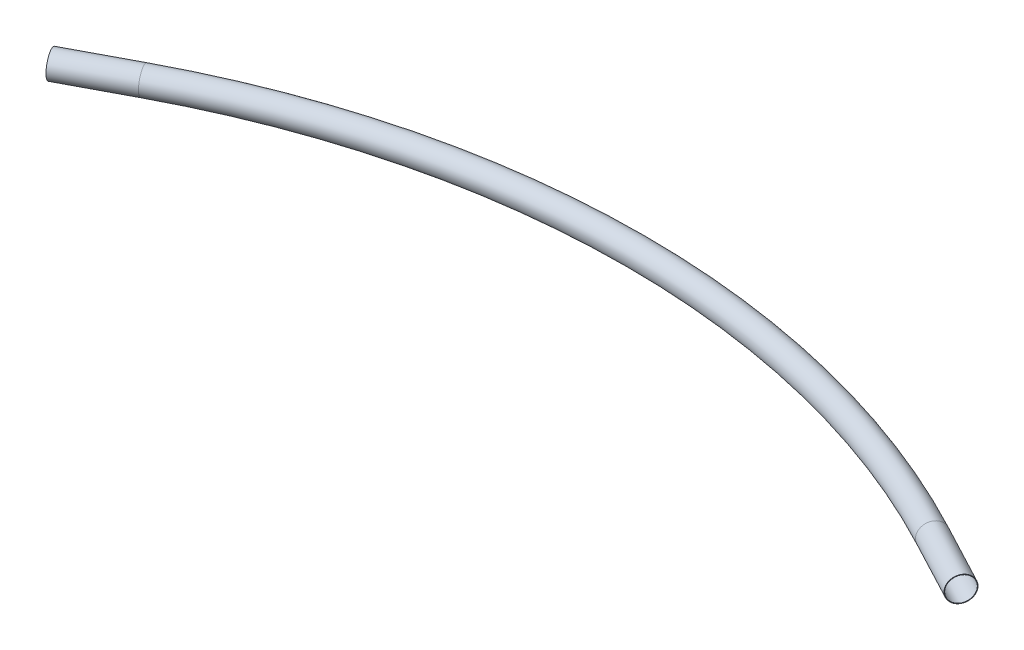
SolidWorks part; units mm, degrees
ref_plane "Front Plane" through (0, 0, 0) normal (0, 0, 1) x (1, 0, 0)
ref_plane "Top Plane" through (0, 0, 0) normal (0, 1, 0) x (1, 0, 0)
ref_plane "Right Plane" through (0, 0, 0) normal (1, 0, 0) x (0, 0, -1)
sketch "Pipe_Definition" plane through (0, 0, 0) normal (0, 1, 0) x (1, 0, 0)
  line L0 (0, 0) -> (0, 654.05) construction
  line L1 (-2635.25, 0) -> (2635.25, 0) construction
  line L6 (-2635.25, 0) -> (-3039.3917, -213.7788)
  line L10 (2635.25, 0) -> (3039.3917, -213.7788)
  arc A1 (2635.25, 0) -> (-2635.25, 0) centre (0, -4981.8524) ccw
  dimension "D1" = 457.2
  dimension "D3" = 5270.5
  dimension "D4" = 2715.2024
  dimension "D5" = 6078.7833
  dimension "D2" = 654.05
  dimension "D7" = 5635.9024
  dimension "D6" = 2635.25
other "Structural Member1"
ref_plane "Plane1" through (2635.25, 0, 0) normal (-0.8839, 0, -0.4676) x (-0.4676, 0, 0.8839)
sketch "Sketch12" plane through (2635.25, 0, 0) normal (-0.8839, 0, -0.4676) x (-0.4676, 0, 0.8839)
  circle A0 centre (0, 0) radius 84.1375
  circle A1 centre (0, 0) radius 80.7339
  point P4 (0, 0)
  dimension "D1" = 168.275
  dimension "D2" = 161.4678
equation "\"D2@Sketch12\" = \"D1@Sketch12\" - .134*2"
